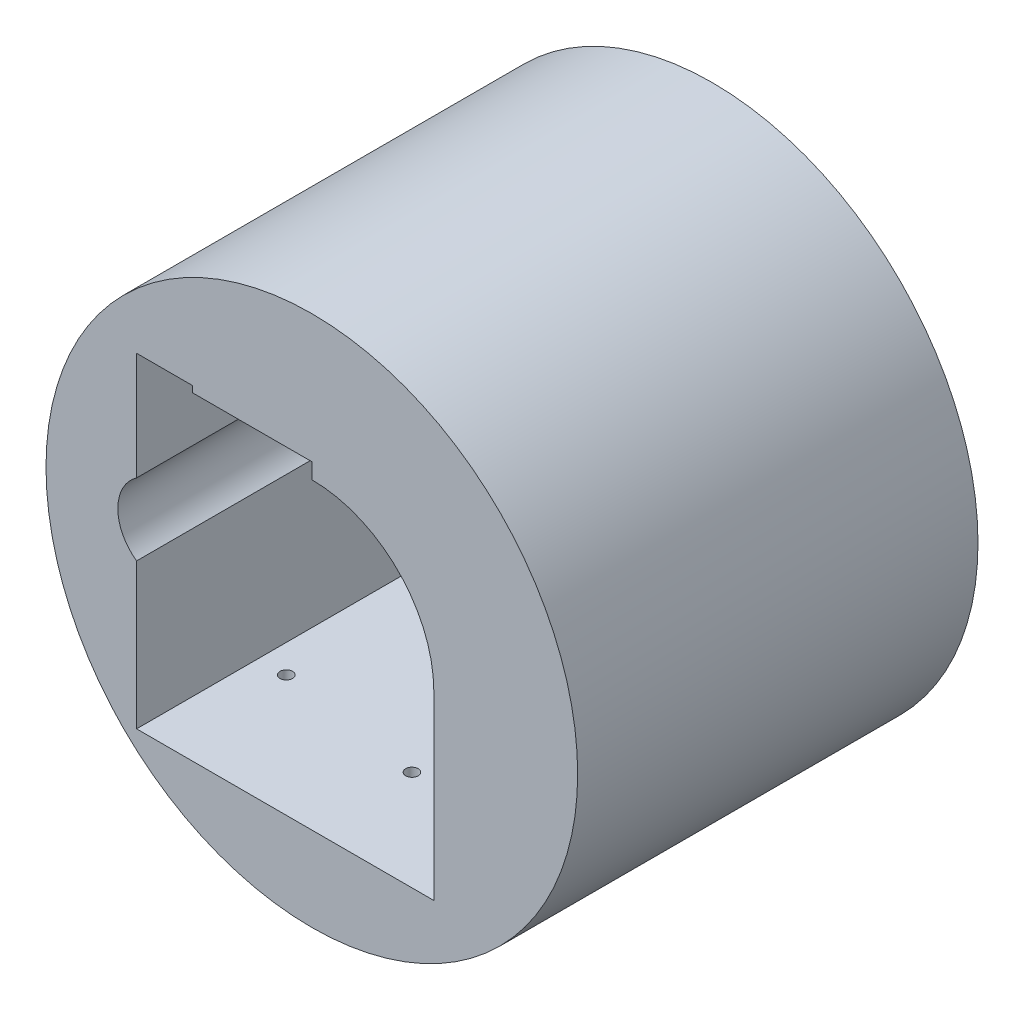
SolidWorks part; units mm, degrees
ref_plane "Front Plane" through (0, 0, 0) normal (0, 0, 1) x (1, 0, 0)
ref_plane "Top Plane" through (0, 0, 0) normal (0, 1, 0) x (1, 0, 0)
ref_plane "Right Plane" through (0, 0, 0) normal (1, 0, 0) x (0, 0, -1)
sketch "Sketch1" plane through (0, 0, -49.1287) normal (0, 0, -1) x (-1, 0, 0)
  line L0 (-13.8011, 15.8348) -> (-13.8011, -4)
  line L1 (-13.8011, 19.2554) -> (-13.8011, -4) construction
  line L2 (-13.8011, -4) -> (-61.3161, -4)
  line L3 (-61.3161, -4) -> (-61.3161, 25)
  line L4 (-13.8011, 34.1652) -> (-13.8011, 47)
  line L5 (-41.8161, 44.5) -> (-41.8161, 47)
  line L6 (-41.8161, 47) -> (-13.8011, 47)
  line L7 (-13.8011, 34.1652) -> (-13.8011, 30.7446)
  line L8 (-13.8011, 28) -> (-13.8011, 40.4952) construction
  line L9 (-13.8011, 15.8348) -> (-13.8011, 19.2554)
  arc A0 (-38.9229, 24.2067) -> (-41.4218, 22.026) centre (-41.8161, 25) ccw construction
  arc A1 (-38.9229, 24.2067) -> (-41.4218, 22.026) centre (-41.8161, 25) ccw construction
  circle A2 centre (-41.8161, 25) radius 42.5
  circle A3 centre (-17.8011, 25) radius 10 construction
  arc A4 (-22.9119, 29.7833) -> (-26.6077, 37.2046) centre (-41.8161, 25) ccw construction
  arc A5 (-41.8161, 44.5) -> (-61.3161, 25) centre (-41.8161, 25) ccw
  arc A9 (-13.8011, 19.2554) -> (-13.8011, 30.7446) centre (-17.8011, 25) ccw
  dimension "D1" = 85
extrude "Boss-Extrude1" add sketch "Sketch1" against normal blind 64
ref_plane "Plane1" through (0, -17.5, 0) normal (0, -1, 0) x (-1, 0, 0)
sketch "Sketch2" plane through (0, -17.5, 0) normal (0, -1, 0) x (-1, 0, 0)
  circle A0 centre (-18.3011, 4.5578) radius 1 construction
  circle A1 centre (-18.3011, 32.5578) radius 1 construction
  circle A2 centre (-18.3011, 4.5578) radius 1
  circle A3 centre (-18.3011, 32.5578) radius 1
  circle A6 centre (-41.8161, 1.1287) radius 1 construction
  circle A7 centre (-41.8161, 1.1287) radius 1
extrude "Cut-Extrude1" cut sketch "Sketch2" against normal up to surface (13.5 mm away) up to face at (37.5586, -4, -17.1287)
sketch "Sketch3" plane through (0, -17.5, 0) normal (0, -1, 0) x (-1, 0, 0)
  circle A0 centre (-41.8161, 1.1287) radius 2.25
  circle A1 centre (-18.3011, 4.5578) radius 2.25
  circle A2 centre (-18.3011, 32.5578) radius 2.25
  dimension "D1" = 4.5
extrude "Cut-Extrude2" cut sketch "Sketch3" against normal blind 5
sketch "Sketch4" plane through (0, -17.5, 0) normal (0, -1, 0) x (-1, 0, 0)
  circle A0 centre (-18.3011, 4.5578) radius 2.25
  circle A1 centre (-18.3011, 32.5578) radius 2.25
extrude "Cut-Extrude3" cut sketch "Sketch4" against normal blind 12
sketch "Sketch5" plane through (0, 0, -49.1287) normal (0, 0, -1) x (-1, 0, 0)
  line L0 (-21.8011, 47) -> (-13.8011, 47)
  line L1 (-13.8011, 47) -> (-13.8011, 48)
  line L7 (-13.8011, 48) -> (-21.8011, 48)
  line L17 (-21.8011, 47) -> (-22.7487, 47)
  line L19 (-21.8011, 48) -> (-22.7487, 48)
  line L20 (-22.7487, 47) -> (-22.7487, 48)
extrude "Cut-Extrude4" cut sketch "Sketch5" against normal through all
